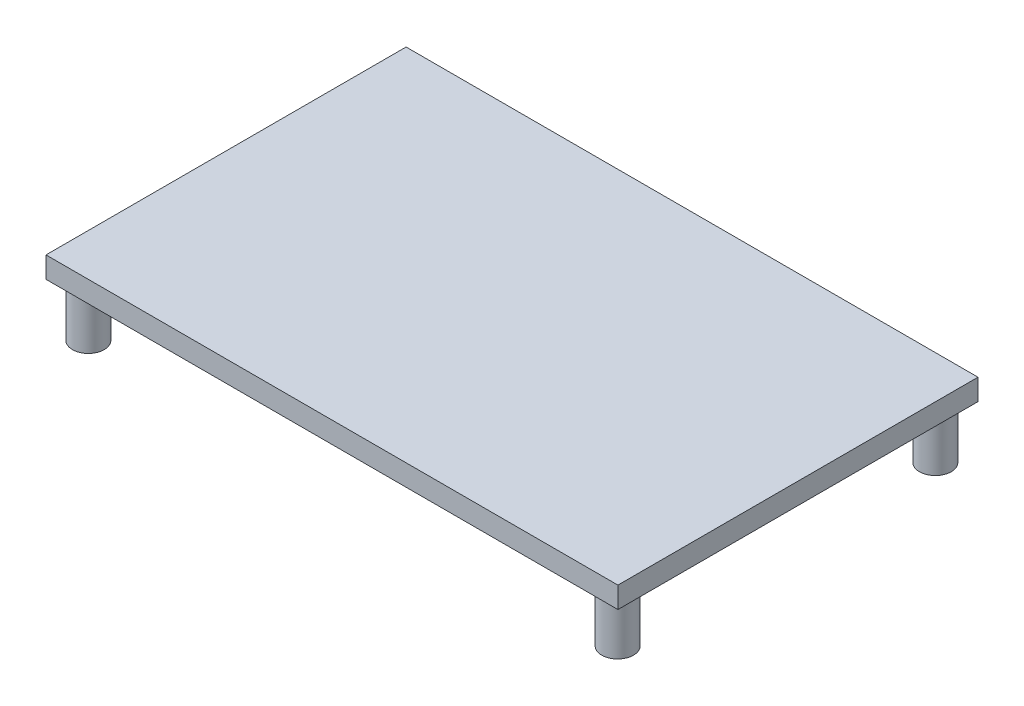
SolidWorks part; units mm, degrees
ref_plane "Front Plane" through (0, 0, 0) normal (0, 0, 1) x (1, 0, 0)
ref_plane "Top Plane" through (0, 0, 0) normal (0, 1, 0) x (1, 0, 0)
ref_plane "Right Plane" through (0, 0, 0) normal (1, 0, 0) x (0, 0, -1)
sketch "Sketch1" plane through (0, 0, 0) normal (0, 1, 0) x (1, 0, 0)
  line L4 (-42.0739, 5.0056) -> (11.9261, 5.0056)
  line L5 (11.9261, 39.0056) -> (11.9261, 5.0056)
  line L6 (-42.0739, 39.0056) -> (11.9261, 39.0056)
  line L7 (-42.0739, 39.0056) -> (-42.0739, 5.0056)
extrude "Boss-Extrude1" add sketch "Sketch1" along normal blind 2 contours L6 L5 L4 L7
sketch "Sketch4" plane through (0, 0, 0) normal (0, -1, 0) x (1, 0, 0)
  circle A4 centre (-40.0739, -7.0056) radius 1.5
  circle A5 centre (9.8979, -7.0067) radius 1.5
  circle A6 centre (9.8979, -37.0067) radius 1.5
  circle A7 centre (-40.0739, -37.0056) radius 1.5
extrude "Boss-Extrude2" add sketch "Sketch4" along normal blind 5 contours A6 | A5 | A4 | A7
hole_wizard "M1.2x0.25 Tapped Hole1" positions "3DSketch5" profile "Sketch7" tap size "M1.2x0.25" standard "ANSI Metric"
sketch3d "3DSketch5"
  line L0 (-40.0739, -5, -7.0056) -> (-40.0739, 0, -7.0056) construction
  line L1 (-40.0739, -5, -37.0056) -> (-40.0739, 0, -37.0056) construction
  line L2 (9.8979, -5, -7.0067) -> (9.8979, 0, -7.0067) construction
  line L3 (9.8979, -5, -37.0067) -> (9.8979, 0, -37.0067) construction
  point P0 (-40.0739, -5, -7.0056)
  point P4 (-40.0739, -5, -37.0056)
  point P8 (9.8979, -5, -7.0067)
  point P12 (9.8979, -5, -37.0067)
sketch "Sketch7" plane through (-40.0739, -5, -7.0056) normal (1, 0, 0) x (0, 0, -1)
  line L0 (0, 0) -> (0, 5.2854)
  line L1 (0, 5.2854) -> (0.475, 5)
  line L2 (0.475, 5) -> (0.475, 0.15)
  line L3 (0.475, 0.15) -> (0.625, 0)
  line L5 (0.625, 0) -> (0, 0)
  line L6 (-0.475, 0.15) -> (-0.625, 0) construction
  line L10 (0, 5.2854) -> (-0.475, 5) construction
  line L11 (0, -6.35) -> (0, 107.95) construction
  dimension "Tap Drill Dia." = 0.95
  dimension "Tap Drill Depth" = 5
  dimension "Near C'Sink Dia." = 1.25
  dimension "Near C'Sink Angle" = 90
  dimension "Drill Angle" = 118
cosmetic thread "Hole Thread1" parameters "D1"=2.4, "D2"=1.2
cosmetic thread "Hole Thread2" parameters "D1"=2.4, "D2"=1.2
cosmetic thread "Hole Thread3" parameters "D1"=2.4, "D2"=1.2
cosmetic thread "Hole Thread4" parameters "D1"=2.4, "D2"=1.2
